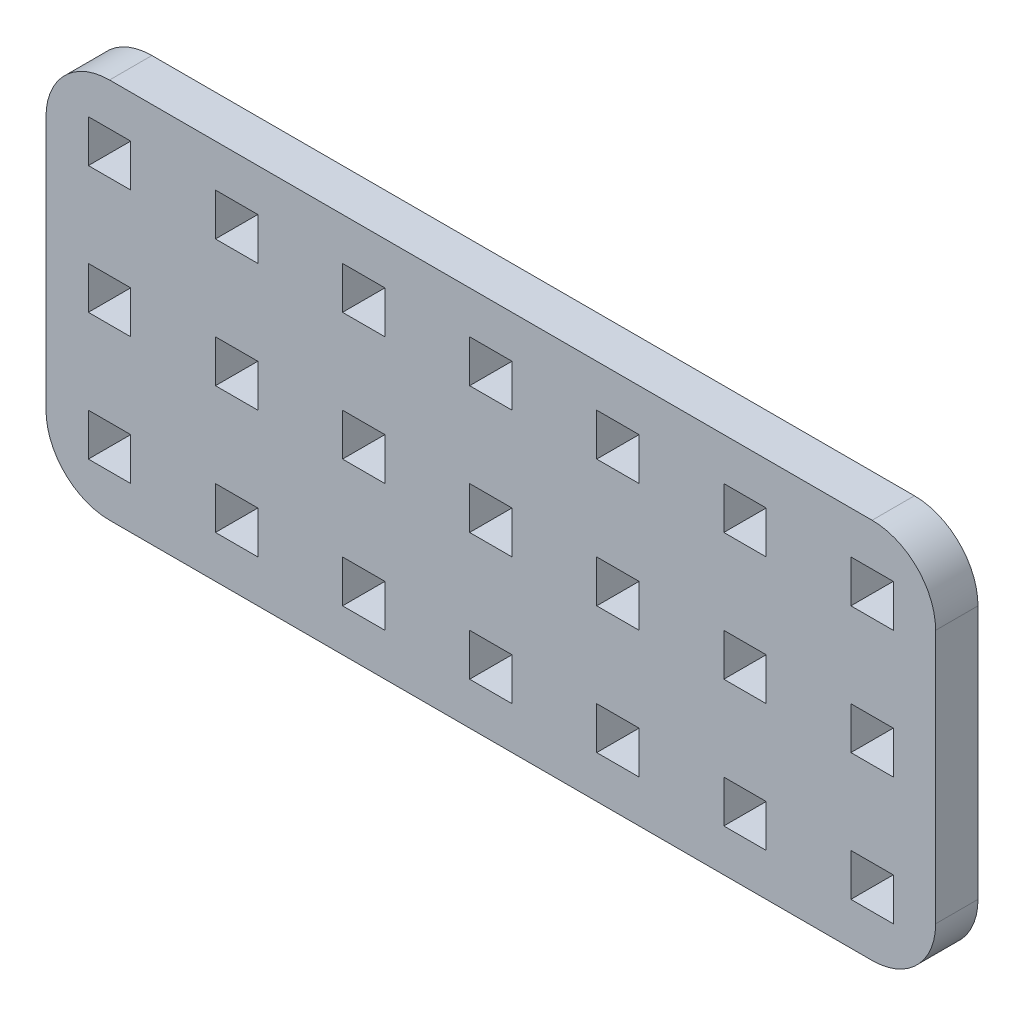
SolidWorks part; units mm, degrees
ref_plane "Alzado" through (0, 0, 0) normal (0, 0, 1) x (1, 0, 0)
ref_plane "Planta" through (0, 0, 0) normal (0, 1, 0) x (1, 0, 0)
ref_plane "Vista lateral" through (0, 0, 0) normal (1, 0, 0) x (0, 0, -1)
sketch "Model" plane through (0, 0, 0) normal (0, 0, 1) x (1, 0, 0)
  line L0 (12.1639, 297.5651) -> (12.1639, 294.5651)
  line L1 (15.1639, 297.5651) -> (12.1639, 297.5651)
  line L2 (15.1639, 294.5651) -> (15.1639, 297.5651)
  line L3 (12.1639, 294.5651) -> (15.1639, 294.5651)
  line L4 (21.1639, 297.5651) -> (21.1639, 294.5651)
  line L5 (24.1639, 297.5651) -> (21.1639, 297.5651)
  line L6 (24.1639, 294.5651) -> (24.1639, 297.5651)
  line L7 (21.1639, 294.5651) -> (24.1639, 294.5651)
  line L8 (30.1639, 297.5651) -> (30.1639, 294.5651)
  line L9 (33.1639, 297.5651) -> (30.1639, 297.5651)
  line L10 (33.1639, 294.5651) -> (33.1639, 297.5651)
  line L11 (30.1639, 294.5651) -> (33.1639, 294.5651)
  line L12 (57.1639, 297.5651) -> (57.1639, 294.5651)
  line L13 (60.1639, 297.5651) -> (57.1639, 297.5651)
  line L14 (60.1639, 294.5651) -> (60.1639, 297.5651)
  line L15 (57.1639, 294.5651) -> (60.1639, 294.5651)
  line L16 (66.1639, 297.5651) -> (66.1639, 294.5651)
  line L17 (69.1639, 297.5651) -> (66.1639, 297.5651)
  line L18 (69.1639, 294.5651) -> (69.1639, 297.5651)
  line L19 (66.1639, 294.5651) -> (69.1639, 294.5651)
  line L20 (12.1639, 279.5651) -> (12.1639, 276.5651)
  line L21 (15.1639, 279.5651) -> (12.1639, 279.5651)
  line L22 (15.1639, 276.5651) -> (15.1639, 279.5651)
  line L23 (12.1639, 276.5651) -> (15.1639, 276.5651)
  line L24 (21.1639, 279.5651) -> (21.1639, 276.5651)
  line L25 (24.1639, 279.5651) -> (21.1639, 279.5651)
  line L26 (24.1639, 276.5651) -> (24.1639, 279.5651)
  line L27 (21.1639, 276.5651) -> (24.1639, 276.5651)
  line L28 (30.1639, 279.5651) -> (30.1639, 276.5651)
  line L29 (33.1639, 279.5651) -> (30.1639, 279.5651)
  line L30 (33.1639, 276.5651) -> (33.1639, 279.5651)
  line L31 (30.1639, 276.5651) -> (33.1639, 276.5651)
  line L32 (57.1639, 279.5651) -> (57.1639, 276.5651)
  line L33 (60.1639, 279.5651) -> (57.1639, 279.5651)
  line L34 (60.1639, 276.5651) -> (60.1639, 279.5651)
  line L35 (57.1639, 276.5651) -> (60.1639, 276.5651)
  line L36 (66.1639, 279.5651) -> (66.1639, 276.5651)
  line L37 (69.1639, 279.5651) -> (66.1639, 279.5651)
  line L38 (69.1639, 276.5651) -> (69.1639, 279.5651)
  line L39 (66.1639, 276.5651) -> (69.1639, 276.5651)
  line L40 (12.1639, 288.5651) -> (12.1639, 285.5651)
  line L41 (15.1639, 288.5651) -> (12.1639, 288.5651)
  line L42 (15.1639, 285.5651) -> (15.1639, 288.5651)
  line L43 (12.1639, 285.5651) -> (15.1639, 285.5651)
  line L44 (21.1639, 288.5651) -> (21.1639, 285.5651)
  line L45 (24.1639, 288.5651) -> (21.1639, 288.5651)
  line L46 (24.1639, 285.5651) -> (24.1639, 288.5651)
  line L47 (21.1639, 285.5651) -> (24.1639, 285.5651)
  line L48 (30.1639, 288.5651) -> (30.1639, 285.5651)
  line L49 (33.1639, 288.5651) -> (30.1639, 288.5651)
  line L50 (33.1639, 285.5651) -> (33.1639, 288.5651)
  line L51 (30.1639, 285.5651) -> (33.1639, 285.5651)
  line L52 (57.1639, 288.5651) -> (57.1639, 285.5651)
  line L53 (60.1639, 288.5651) -> (57.1639, 288.5651)
  line L54 (60.1639, 285.5651) -> (60.1639, 288.5651)
  line L55 (57.1639, 285.5651) -> (60.1639, 285.5651)
  line L56 (66.1639, 288.5651) -> (66.1639, 285.5651)
  line L57 (69.1639, 288.5651) -> (66.1639, 288.5651)
  line L58 (69.1639, 285.5651) -> (69.1639, 288.5651)
  line L59 (66.1639, 285.5651) -> (69.1639, 285.5651)
  line L60 (39.1639, 297.5651) -> (39.1639, 294.5651)
  line L61 (42.1639, 297.5651) -> (39.1639, 297.5651)
  line L62 (42.1639, 294.5651) -> (42.1639, 297.5651)
  line L63 (39.1639, 294.5651) -> (42.1639, 294.5651)
  line L64 (48.1639, 297.5651) -> (48.1639, 294.5651)
  line L65 (51.1639, 297.5651) -> (48.1639, 297.5651)
  line L66 (51.1639, 294.5651) -> (51.1639, 297.5651)
  line L67 (48.1639, 294.5651) -> (51.1639, 294.5651)
  line L68 (39.1639, 279.5651) -> (39.1639, 276.5651)
  line L69 (42.1639, 279.5651) -> (39.1639, 279.5651)
  line L70 (42.1639, 276.5651) -> (42.1639, 279.5651)
  line L71 (39.1639, 276.5651) -> (42.1639, 276.5651)
  line L72 (48.1639, 279.5651) -> (48.1639, 276.5651)
  line L73 (51.1639, 279.5651) -> (48.1639, 279.5651)
  line L74 (51.1639, 276.5651) -> (51.1639, 279.5651)
  line L75 (48.1639, 276.5651) -> (51.1639, 276.5651)
  line L76 (39.1639, 288.5651) -> (39.1639, 285.5651)
  line L77 (42.1639, 288.5651) -> (39.1639, 288.5651)
  line L78 (42.1639, 285.5651) -> (42.1639, 288.5651)
  line L79 (39.1639, 285.5651) -> (42.1639, 285.5651)
  line L80 (48.1639, 288.5651) -> (48.1639, 285.5651)
  line L81 (51.1639, 288.5651) -> (48.1639, 288.5651)
  line L82 (51.1639, 285.5651) -> (51.1639, 288.5651)
  line L83 (48.1639, 285.5651) -> (51.1639, 285.5651)
  line L84 (13.6639, 300.5651) -> (67.6639, 300.5651)
  line L85 (13.6639, 273.5651) -> (67.6639, 273.5651)
  line L86 (9.1639, 296.0651) -> (9.1639, 278.0651)
  line L87 (72.1639, 296.0651) -> (72.1639, 278.0651)
  arc A0 (72.1639, 296.0651) -> (67.6639, 300.5651) centre (67.6639, 296.0651) ccw
  arc A1 (67.6639, 273.5651) -> (72.1639, 278.0651) centre (67.6639, 278.0651) ccw
  arc A2 (13.6639, 300.5651) -> (9.1639, 296.0651) centre (13.6639, 296.0651) ccw
  arc A3 (9.1639, 278.0651) -> (13.6639, 273.5651) centre (13.6639, 278.0651) ccw
extrude "Saliente-Extruir1" add sketch "Model" along normal blind 3
